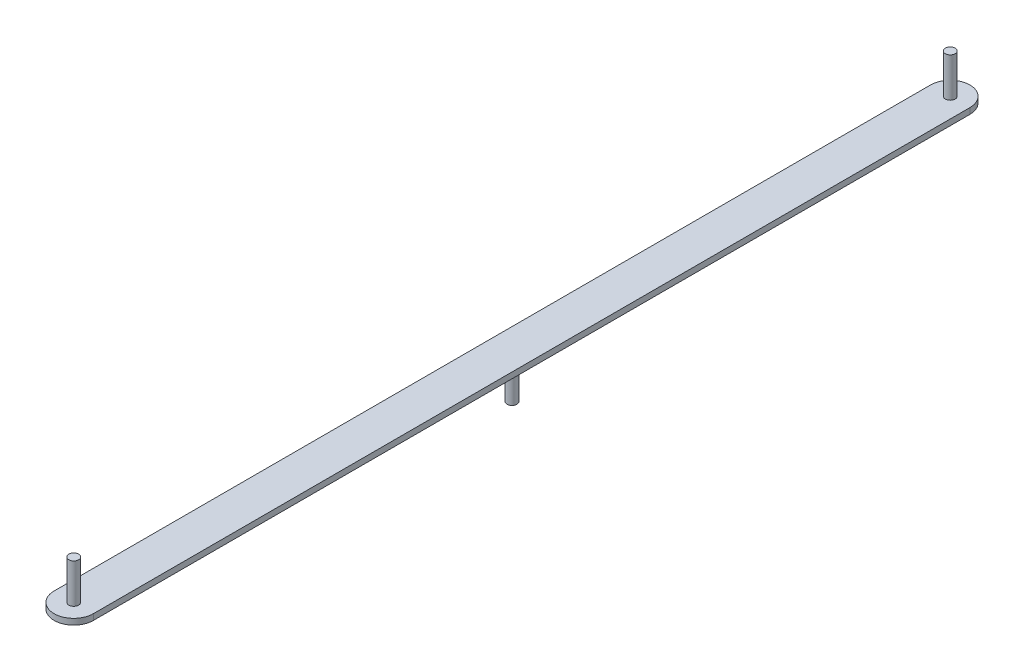
SolidWorks part; units mm, degrees
ref_plane "Front Plane" through (0, 0, 0) normal (0, 0, 1) x (1, 0, 0)
ref_plane "Top Plane" through (0, 0, 0) normal (0, 1, 0) x (1, 0, 0)
ref_plane "Right Plane" through (0, 0, 0) normal (1, 0, 0) x (0, 0, -1)
sketch "Sketch1" plane through (0, 0, 0) normal (0, 1, 0) x (1, 0, 0)
  line L2 (-25.7692, 365.6154) -> (-25.7692, -80.3846)
  line L4 (-5.7692, 365.6154) -> (-5.7692, -80.3846)
  arc A0 (-25.7692, 365.6154) -> (-5.7692, 365.6154) centre (-15.7692, 365.6154) cw
  arc A1 (-25.7692, -80.3846) -> (-5.7692, -80.3846) centre (-15.7692, -80.3846) ccw
  dimension "D1" = 20
  dimension "D2" = 446
extrude "Boss-Extrude1" add sketch "Sketch1" along normal blind 3
sketch "Sketch2" plane through (0, 3, 0) normal (0, 1, 0) x (1, 0, 0)
  circle A0 centre (-15.7692, -80.3846) radius 2.5
  circle A2 centre (-15.7692, 365.6154) radius 2.5
  arc A3 (-25.7692, -80.3846) -> (-5.7692, -80.3846) centre (-15.7692, -80.3846) ccw construction
  arc A4 (-5.7692, 365.6154) -> (-25.7692, 365.6154) centre (-15.7692, 365.6154) ccw construction
  dimension "D1" = 5
  dimension "D2" = 5
extrude "Boss-Extrude2" add sketch "Sketch2" along normal blind 20
sketch "Sketch3" plane through (0, 0, 0) normal (0, -1, 0) x (1, 0, 0)
  line L0 (-25.7692, -365.6154) -> (-25.7692, 80.3846) construction
  circle A0 centre (-15.7692, -142.6154) radius 5
  arc A1 (-5.7692, 80.3846) -> (-25.7692, 80.3846) centre (-15.7692, 80.3846) ccw construction
  dimension "D1" = 10
  dimension "D3" = 223
  dimension "D2" = 10
extrude "Boss-Extrude3" add sketch "Sketch3" along normal blind 2
sketch "Sketch4" plane through (0, -2, 0) normal (0, -1, 0) x (1, 0, 0)
  circle A0 centre (-15.7692, -142.6154) radius 2.5
  circle A1 centre (-15.7692, -142.6154) radius 5 construction
  dimension "D1" = 5
extrude "Boss-Extrude4" add sketch "Sketch4" along normal blind 18
